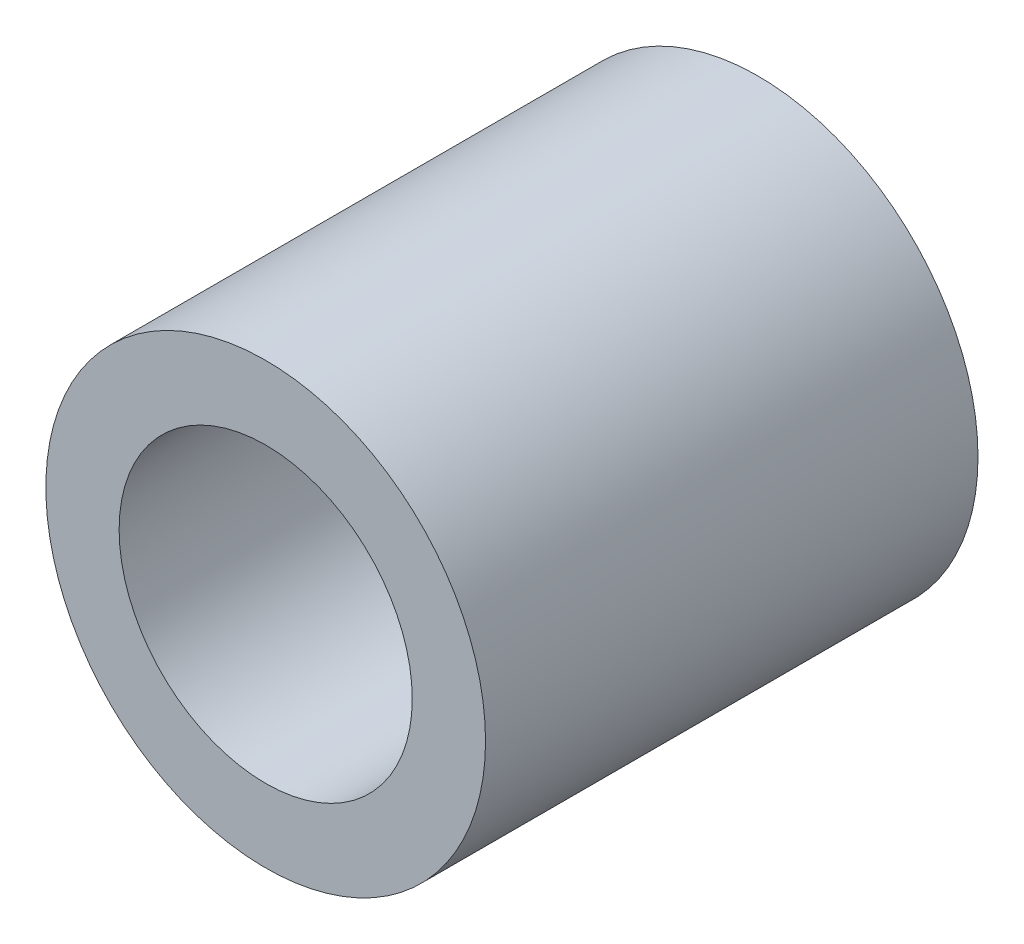
SolidWorks part; units mm, degrees
material "PET"
ref_plane "Front Plane" through (0, 0, 0) normal (0, 0, 1) x (1, 0, 0)
ref_plane "Top Plane" through (0, 0, 0) normal (0, 1, 0) x (1, 0, 0)
ref_plane "Right Plane" through (0, 0, 0) normal (1, 0, 0) x (0, 0, -1)
sketch "Sketch1" plane through (0, 0, 0) normal (0, 0, 1) x (1, 0, 0)
  circle A0 centre (0, 0) radius 6.35
  circle A1 centre (0, 0) radius 9.525
  dimension "D1" = 12.7
  dimension "D2" = 19.05
extrude "Boss-Extrude1" add sketch "Sketch1" along normal mid plane 21.336
